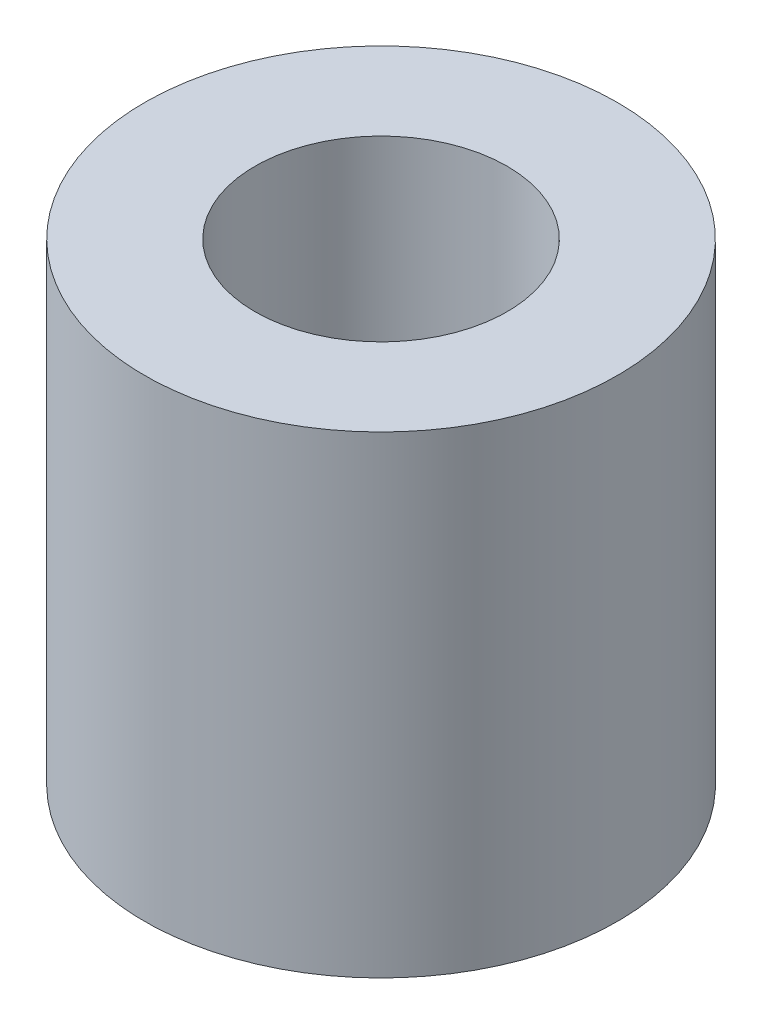
SolidWorks part; units mm, degrees
ref_plane "Front Plane" through (0, 0, 0) normal (0, 0, 1) x (1, 0, 0)
ref_plane "Top Plane" through (0, 0, 0) normal (0, 1, 0) x (1, 0, 0)
ref_plane "Right Plane" through (0, 0, 0) normal (1, 0, 0) x (0, 0, -1)
sketch "Sketch1" plane through (0, 0, 0) normal (0, 1, 0) x (1, 0, 0)
  circle A0 centre (0, 0) radius 4.7625
  circle A1 centre (0, 0) radius 2.54
  dimension "D1" = 9.525
  dimension "D2" = 5.08
extrude "Boss-Extrude1" add sketch "Sketch1" along normal blind 9.525
